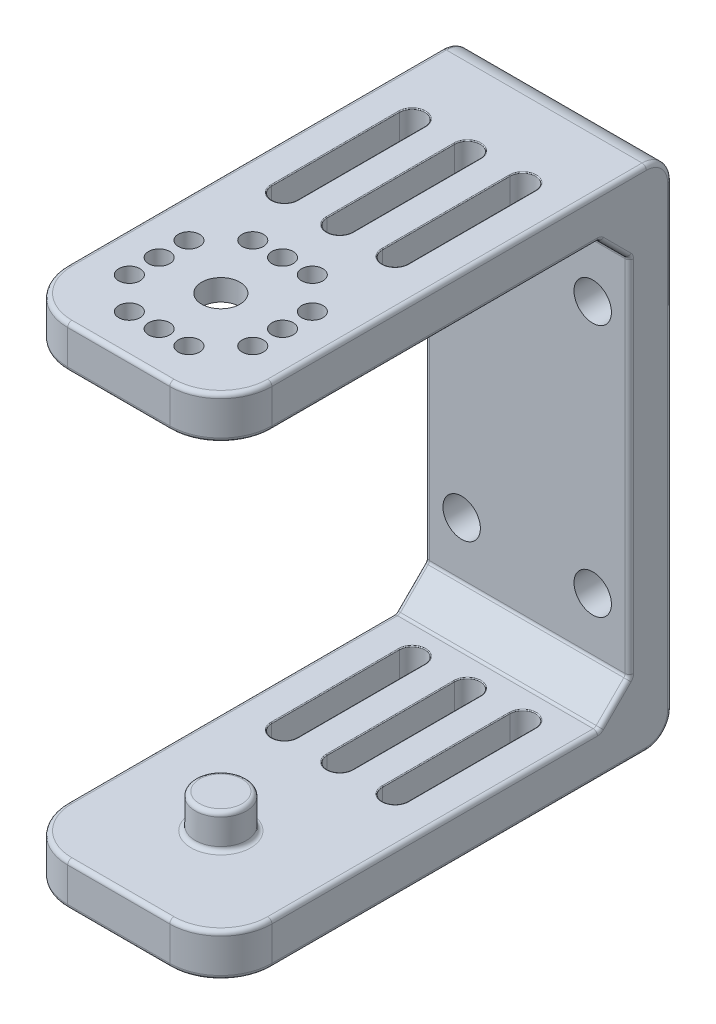
SolidWorks part; units mm, degrees
ref_plane "Front Plane" through (0, 0, 0) normal (0, 0, 1) x (1, 0, 0)
ref_plane "Top Plane" through (0, 0, 0) normal (0, 1, 0) x (1, 0, 0)
ref_plane "Right Plane" through (0, 0, 0) normal (1, 0, 0) x (0, 0, -1)
sketch "Sketch1" plane through (0, 0, 0) normal (1, 0, 0) x (0, 0, -1)
  line L0 (0, 59.7) -> (0, 0)
  line L1 (0, 0) -> (-53, 0)
  line L2 (-53, 0) -> (-53, 5)
  line L3 (-53, 5) -> (-8.5355, 5)
  line L4 (-5, 8.5355) -> (-5, 51.1645)
  line L5 (-8.5355, 54.7) -> (-53, 54.7)
  line L6 (-53, 54.7) -> (-53, 59.7)
  line L7 (-53, 59.7) -> (0, 59.7)
  line L8 (-8.5355, 54.7) -> (-5, 51.1645)
  line L9 (-5, 29.85) -> (0, 29.85) construction
  line L10 (-8.5355, 5) -> (-5, 8.5355)
  dimension "D1" = 49.7
  dimension "D2" = 5
  dimension "D3" = 5
  dimension "D4" = 45
  dimension "50" = 53
  dimension "D5" = 5
extrude "Boss-Extrude1" add sketch "Sketch1" along normal blind 24
sketch "Sketch2" plane through (0, 54.7, 0) normal (0, -1, 0) x (1, 0, 0)
  line L0 (24, 53) -> (0, 53) construction
  line L1 (12, 53) -> (12, 0) construction
  line L2 (24, 0) -> (0, 0) construction
  circle A0 centre (12, 41) radius 10.5
  dimension "D1" = 21
  dimension "D2" = 12
  dimension "D3" = 0
extrude "Cut-Extrude1" cut sketch "Sketch2" against normal blind 2.5
sketch "Sketch4" plane through (0, 57.2, 0) normal (0, -1, 0) x (1, 0, 0)
  circle A0 centre (12, 41) radius 2.25
  circle A1 centre (12, 41) radius 10.5 construction
  circle A2 centre (12, 48.25) radius 1.25
  circle A3 centre (8.5, 48.25) radius 1.25
  circle A4 centre (15.5, 48.25) radius 1.25
  circle A5 centre (19.25, 44.5) radius 1.25
  circle A6 centre (19.25, 41) radius 1.25
  circle A7 centre (19.25, 37.5) radius 1.25
  circle A8 centre (15.5, 33.75) radius 1.25
  circle A9 centre (12, 33.75) radius 1.25
  circle A10 centre (8.5, 33.75) radius 1.25
  circle A11 centre (4.75, 37.5) radius 1.25
  circle A12 centre (4.75, 41) radius 1.25
  circle A13 centre (4.75, 44.5) radius 1.25
  dimension "D1" = 4.5
  dimension "D2" = 0
  dimension "D3" = 2.5
  dimension "D4" = 7.25
  dimension "D5" = 3.5
  dimension "D6" = 3.5
  dimension "D7" = 4
extrude "Cut-Extrude2" cut sketch "Sketch4" against normal blind 10
fillet "Fillet2" radius 6 4 edges at (24, 2.5, 53) (0, 2.5, 53) (24, 57.2, 53) (0, 57.2, 53)
fillet "Fillet3" radius 3 2 edges at (12, 0, 0) (12, 59.7, 0)
sketch "Sketch7" plane through (0, 0, 0) normal (0, 0, -1) x (-1, 0, 0)
  line L0 (-24, 3) -> (-24, 56.7) construction
  line L6 (-24, 29.85) -> (0, 29.85) construction
  line L7 (-12, 56.7) -> (-12, 3) construction
  line L8 (0, 56.7) -> (-24, 56.7) construction
  line L9 (-24, 3) -> (0, 3) construction
  line L10 (0, 3) -> (0, 56.7) construction
  circle A4 centre (-19.7, 44.7) radius 2.2
  circle A5 centre (-19.7, 15) radius 2.2
  circle A6 centre (-4.3, 15) radius 2.2
  circle A7 centre (-4.3, 44.7) radius 2.2
  dimension "D2" = 4.4
  dimension "D3" = 29.7
  dimension "D1" = 15.4
extrude "Cut-Extrude3" cut sketch "Sketch7" against normal blind 7
sketch "Sketch8" plane through (0, 5, 0) normal (0, 1, 0) x (1, 0, 0)
  line L0 (12, -53) -> (12, -5) construction
  line L1 (18, -53) -> (6, -53) construction
  line L2 (24, -5) -> (0, -5) construction
  circle A0 centre (12, -41) radius 3
  dimension "D1" = 6
  dimension "D2" = 12
extrude "Boss-Extrude2" add sketch "Sketch8" along normal blind 4
fillet "Fillet4" radius 0.5 38 edges at (12, 5, 38) (12, 9, 44) (24, 54.7, 27.7678) (22.2426, 54.7, 51.2426) (12, 54.7, 53) (1.7574, 54.7, 51.2426) (1.7574, 0, 51.2426) (12, 0, 53) (22.2426, 0, 51.2426) (24, 0, 25) (24, 0.8787, 0.8787) (24, 29.85, 0) (24, 58.8213, 0.8787) (24, 59.7, 25) (22.2426, 59.7, 51.2426) (12, 59.7, 53) (1.7574, 59.7, 51.2426) (24, 5, 27.7678) (22.2426, 5, 51.2426) (1.7574, 5, 51.2426) (0, 58.8213, 0.8787) (0, 59.7, 25) (0, 54.7, 27.7678) (0, 29.85, 5) (0, 5, 27.7678) (0, 0, 25) (0, 0.8787, 0.8787) (0, 29.85, 0) (24, 29.85, 5) (12, 5, 53) (0, 52.9322, 6.7678) (0, 6.7678, 6.7678) (24, 6.7678, 6.7678) (12, 54.7, 8.5355) (24, 52.9322, 6.7678) (12, 51.1645, 5) (12, 5, 8.5355) (12, 8.5355, 5)
sketch "Sketch9" plane through (0, 54.7, 0) normal (0, -1, 0) x (1, 0, 0)
  line L0 (0.5, 19.5178) -> (23.5, 19.5178) construction
  line L1 (0.5, 47) -> (0.5, 8.7426) construction
  line L2 (23.5, 8.7426) -> (23.5, 47) construction
  line L3 (12, 5) -> (12, 30.5) construction
  line L4 (23.5, 5) -> (0.5, 5) construction
  line L5 (12, 19.5178) -> (13.5, 12.0178) construction
  line L7 (10.5, 12.0178) -> (10.5, 27.0178)
  line L9 (13.5, 12.0178) -> (13.5, 27.0178)
  line L10 (12, 19.5178) -> (13.5, 27.0178) construction
  line L11 (10.5, 27.0178) -> (12, 19.5178) construction
  line L12 (10.5, 12.0178) -> (12, 19.5178) construction
  line L13 (12, 30.5) -> (23.5, 30.5) construction
  line L14 (20, 12.0178) -> (20, 27.0178)
  line L15 (17, 12.0178) -> (17, 27.0178)
  line L16 (7, 12.0178) -> (7, 27.0178)
  line L17 (4, 12.0178) -> (4, 27.0178)
  line L18 (23.5, 30.5) -> (23.5, 8.5355) construction
  line L19 (23.5, 8.7426) -> (23.5, 47) construction
  line L21 (23.5, 8.5355) -> (0.5, 8.5355) construction
  circle A0 centre (12, 41) radius 10.5 construction
  arc A1 (13.5, 27.0178) -> (10.5, 27.0178) centre (12, 27.0178) ccw
  arc A2 (13.5, 12.0178) -> (10.5, 12.0178) centre (12, 12.0178) cw
  arc A3 (20, 27.0178) -> (17, 27.0178) centre (18.5, 27.0178) ccw
  arc A4 (20, 12.0178) -> (17, 12.0178) centre (18.5, 12.0178) cw
  arc A5 (4, 12.0178) -> (7, 12.0178) centre (5.5, 12.0178) ccw
  arc A6 (4, 27.0178) -> (7, 27.0178) centre (5.5, 27.0178) cw
  point P13 (12, 19.5178)
  point P19 (13.5, 19.5178)
  point P22 (10.5, 19.5178)
  dimension "D1" = 3
  dimension "D2" = 15
  dimension "D5" = 6.5
  dimension "D4" = 2
extrude "Cut-Extrude4" cut sketch "Sketch9" against normal mid plane 130
fillet "Fillet5" radius 0.1 48 edges at (18.5, 0, 10.5178) (20, 0, 19.5178) (18.5, 0, 28.5178) (12, 0, 10.5178) (13.5, 0, 19.5178) (12, 0, 28.5178) (5.5, 0, 10.5178) (7, 0, 19.5178) (5.5, 0, 28.5178) (5.5, 5, 10.5178) (4, 5, 19.5178) (5.5, 5, 28.5178) (12, 5, 28.5178) (13.5, 5, 19.5178) (12, 5, 10.5178) (18.5, 5, 28.5178) (20, 5, 19.5178) (18.5, 5, 10.5178) (18.5, 59.7, 28.5178) (20, 59.7, 19.5178) (18.5, 59.7, 10.5178) (12, 59.7, 28.5178) (13.5, 59.7, 19.5178) (12, 59.7, 10.5178) (5.5, 59.7, 28.5178) (7, 59.7, 19.5178) (5.5, 59.7, 10.5178) (18.5, 54.7, 10.5178) (20, 54.7, 19.5178) (18.5, 54.7, 28.5178) (12, 54.7, 10.5178) (13.5, 54.7, 19.5178) (12, 54.7, 28.5178) (5.5, 54.7, 10.5178) (7, 54.7, 19.5178) (5.5, 54.7, 28.5178) (17, 0, 19.5178) (10.5, 0, 19.5178) (4, 0, 19.5178) (7, 5, 19.5178) (10.5, 5, 19.5178) (17, 5, 19.5178) (17, 59.7, 19.5178) (10.5, 59.7, 19.5178) (4, 59.7, 19.5178) (17, 54.7, 19.5178) (10.5, 54.7, 19.5178) (4, 54.7, 19.5178)
